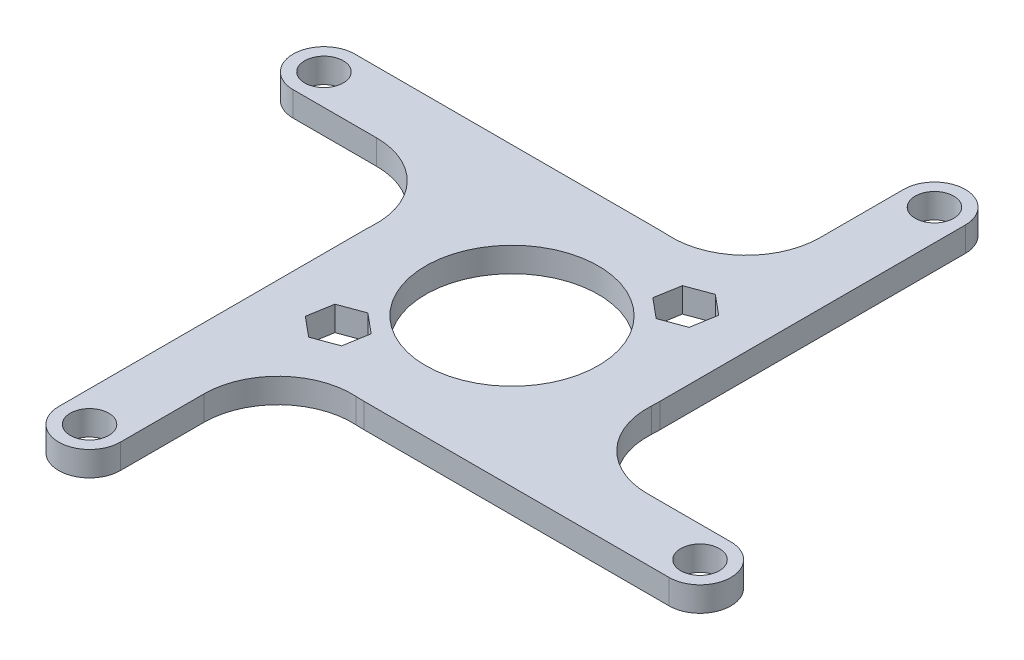
SolidWorks part; units mm, degrees
material "Plain Carbon Steel"
ref_plane "Front Plane" through (0, 0, 0) normal (0, 0, 1) x (1, 0, 0)
ref_plane "Top Plane" through (0, 0, 0) normal (0, 1, 0) x (1, 0, 0)
ref_plane "Right Plane" through (0, 0, 0) normal (1, 0, 0) x (0, 0, -1)
sketch "Sketch1" plane through (0, 0, 0) normal (0, 1, 0) x (1, 0, 0)
  line L0 (-49.4773, 19) -> (-13.0695, 5.0189) construction
  line L1 (-49.4773, 24) -> (0, 24)
  line L2 (-49.4773, 14) -> (-19.4936, 14)
  line L3 (24, 49.4773) -> (24, 0)
  line L4 (14, 49.4773) -> (14, 19.4936)
  line L5 (49.4773, -24) -> (0, -24)
  line L6 (49.4773, -14) -> (19.4936, -14)
  line L7 (-49.4773, 14) -> (-49.4773, 15.875) construction
  line L8 (-49.4773, 15.875) -> (-49.4773, 22.125) construction
  line L9 (-49.4773, 22.125) -> (-49.4773, 24) construction
  line L10 (0, 14) -> (0, 24) construction
  line L11 (-24, -49.4773) -> (-24, 0)
  line L12 (-14, -49.4773) -> (-14, -19.4936)
  line L13 (19, 49.4773) -> (-19, -49.4773) construction
  circle A0 centre (0, 0) radius 14
  arc A1 (-24, -49.4773) -> (-14, -49.4773) centre (-19, -49.4773) ccw
  circle A2 centre (-19, -49.4773) radius 3.125
  arc A3 (-14, -19.4936) -> (0, -24) centre (0, 0) ccw
  arc A6 (14, 19.4936) -> (0, 24) centre (0, 0) ccw
  arc A7 (-49.4773, 24) -> (-49.4773, 14) centre (-49.4773, 19) ccw
  arc A8 (24, 49.4773) -> (14, 49.4773) centre (19, 49.4773) ccw
  arc A9 (49.4773, -24) -> (49.4773, -14) centre (49.4773, -19) ccw
  circle A10 centre (-49.4773, 19) radius 3.125
  circle A11 centre (19, 49.4773) radius 3.125
  circle A12 centre (49.4773, -19) radius 3.125
  arc A13 (19.4936, -14) -> (24, 0) centre (0, 0) ccw
  arc A14 (-19.4936, 14) -> (-24, 0) centre (0, 0) ccw
  circle A15 centre (0, 0) radius 48 construction
  point P15 (-24, 0)
  point P33 (0, 0)
  dimension "D2" = 28
  dimension "D3" = 6.25
  dimension "D4" = 106
  dimension "D5" = 5
  dimension "D6" = 10
  dimension "D1" = 4
extrude "Boss-Extrude1" add sketch "Sketch1" along normal blind 4
fillet "Fillet1" radius 12 4 edges at (19.4936, 2, 14) (14, 2, -19.4936) (-19.4936, 2, -14) (-14, 2, 19.4936)
sketch "Sketch3" plane through (0, 4, 0) normal (0, 1, 0) x (1, 0, 0)
  line L0 (12.7823, 15.3822) -> (-12.7823, -15.3822) construction
  line L3 (24, 0) -> (24, 49.4773) construction
  line L5 (9.5852, 18.039) -> (8.8829, 13.9418)
  line L6 (8.8829, 13.9418) -> (12.0801, 11.285)
  line L7 (12.0801, 11.285) -> (15.9794, 12.7255)
  line L8 (15.9794, 12.7255) -> (16.6817, 16.8226)
  line L9 (16.6817, 16.8226) -> (13.4846, 19.4794)
  line L10 (13.4846, 19.4794) -> (9.5852, 18.039)
  line L11 (-15.9794, -12.7255) -> (-16.6817, -16.8226)
  line L12 (-16.6817, -16.8226) -> (-13.4846, -19.4794)
  line L13 (-13.4846, -19.4794) -> (-9.5852, -18.039)
  line L14 (-9.5852, -18.039) -> (-8.8829, -13.9418)
  line L15 (-8.8829, -13.9418) -> (-12.0801, -11.285)
  line L16 (-12.0801, -11.285) -> (-15.9794, -12.7255)
  circle A0 centre (12.7823, 15.3822) radius 1.5 construction
  circle A1 centre (-12.7823, -15.3822) radius 1.5 construction
  circle A2 centre (12.7823, 15.3822) radius 11.2177 construction
  arc A5 (1.3333, 23.9629) -> (14, 35.9444) centre (2, 35.9444) ccw construction
  circle A6 centre (12.7823, 15.3822) radius 3.6 construction
  circle A7 centre (-12.7823, -15.3822) radius 3.6 construction
  point P4 (0, 0)
  dimension "D1" = 40
  dimension "D2" = 3
  dimension "D3" = 7.2
extrude "Cut-Extrude2" cut sketch "Sketch3" against normal blind 10
